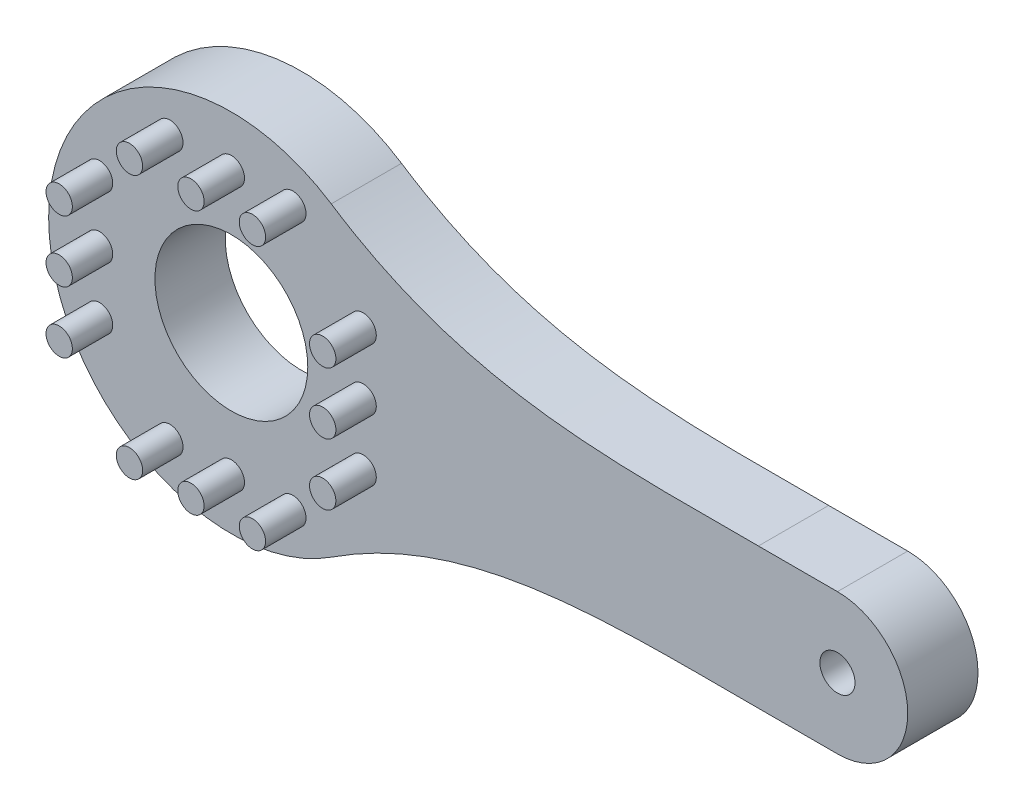
SolidWorks part; units mm, degrees
ref_plane "Front Plane" through (0, 0, 0) normal (0, 0, 1) x (1, 0, 0)
ref_plane "Top Plane" through (0, 0, 0) normal (0, 1, 0) x (1, 0, 0)
ref_plane "Right Plane" through (0, 0, 0) normal (1, 0, 0) x (0, 0, -1)
sketch "Sketch1" plane through (0, 0, 0) normal (0, 0, 1) x (1, 0, 0)
  line L0 (0, 0) -> (52.669, 0) construction
  line L1 (30, 4) -> (34.5, 4)
  line L2 (30, -4) -> (34.5, -4)
  arc A0 (5.6862, 8.7079) -> (5.6862, -8.7079) centre (0, 0) ccw
  circle A1 centre (0, 0) radius 4.35
  arc A2 (34.5, 4) -> (34.5, -4) centre (34.5, 0) cw
  circle A3 centre (34.5, 0) radius 1
  spline S0 degree 3 poles (5.6862, 8.7079) (13.4104, 3.664) (21.2669, 4) (30, 4) knots 0 0 0 0 1 1 1 1
  spline S1 degree 3 poles (5.6862, -8.7079) (13.4104, -3.664) (21.2669, -4) (30, -4) knots 0 0 0 0 1 1 1 1
  dimension "D1" = 20.8
  dimension "D2" = 8.7
  dimension "D8" = 34.5
  dimension "D7" = 2
  dimension "D3" = 4
  dimension "D4" = 4.5
  dimension "D5" = 17.1959
  dimension "D6" = 30
extrude "Boss-Extrude1" add sketch "Sketch1" along normal blind 4
sketch "Sketch2" plane through (0, 0, 4) normal (0, 0, 1) x (1, 0, 0)
  line L0 (0, -55) -> (0, 55) construction
  line L1 (55, 0) -> (-55, 0) construction
  circle A0 centre (0, 0) radius 10.4 construction
  circle A1 centre (0, 0) radius 4.35 construction
  circle A2 centre (0, 7.5) radius 0.75
  circle A3 centre (3.5, 7.5) radius 0.75
  circle A4 centre (-3.5, 7.5) radius 0.75
  circle A5 centre (3.5, -7.5) radius 0.75
  circle A6 centre (0, -7.5) radius 0.75
  circle A7 centre (-3.5, -7.5) radius 0.75
  circle A8 centre (7.5, 0) radius 0.75
  circle A9 centre (7.5, 3.5) radius 0.75
  circle A10 centre (7.5, -3.5) radius 0.75
  circle A11 centre (-7.5, -3.5) radius 0.75
  circle A12 centre (-7.5, 0) radius 0.75
  circle A13 centre (-7.5, 3.5) radius 0.75
  dimension "D1" = 20.8
  dimension "D2" = 8.7
  dimension "D3" = 1.5
  dimension "D5" = 1.5
  dimension "D9" = 1.5
  dimension "D12" = 1.5
  dimension "D4" = 7.5
  dimension "D6" = 3.5
  dimension "D7" = 0
  dimension "D8" = 0
  dimension "D10" = 7.5
  dimension "D11" = 0
  dimension "D13" = 3.5
  dimension "D14" = 0
extrude "Boss-Extrude2" add sketch "Sketch2" along normal blind 2.3
sketch "Sketch4" plane through (0, 0, 4) normal (0, 0, 1) x (1, 0, 0)
  point P0 (0, 0)
